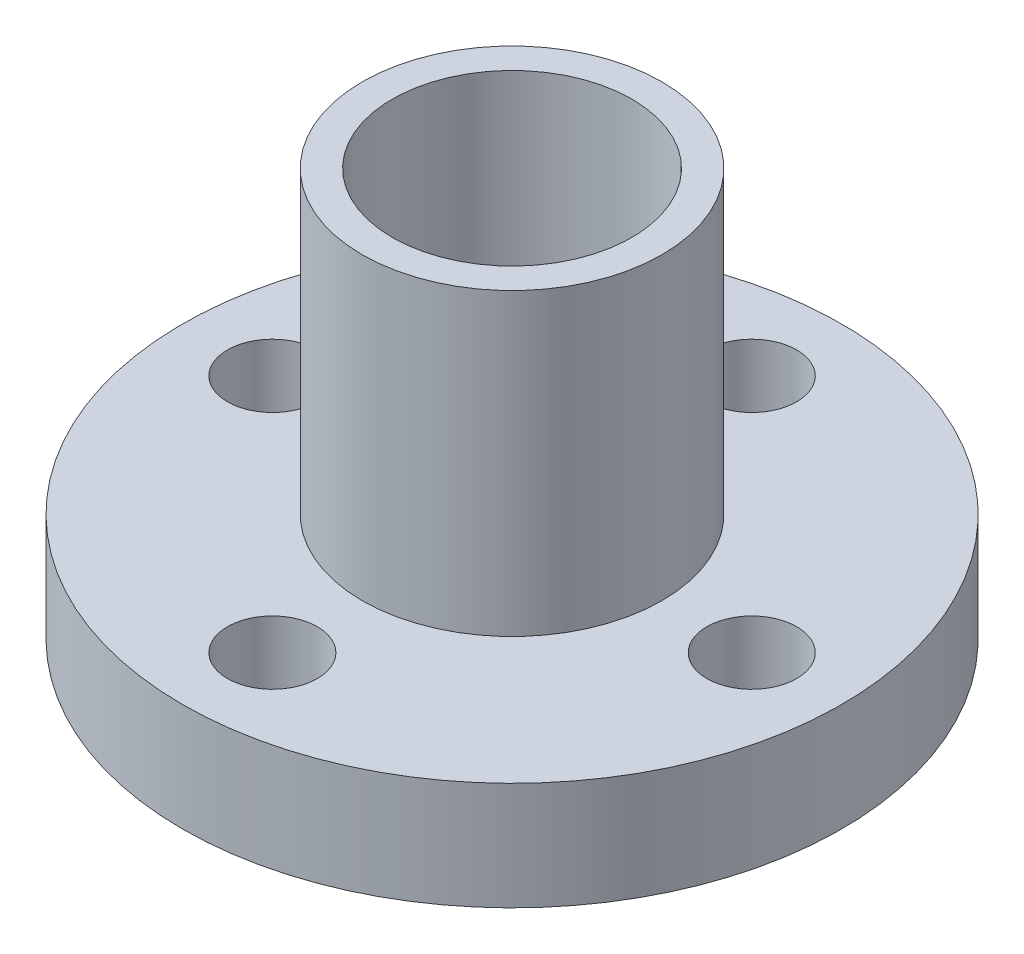
SolidWorks part; units mm, degrees
ref_plane "Front Plane" through (0, 0, 0) normal (0, 0, 1) x (1, 0, 0)
ref_plane "Top Plane" through (0, 0, 0) normal (0, 1, 0) x (1, 0, 0)
ref_plane "Right Plane" through (0, 0, 0) normal (1, 0, 0) x (0, 0, -1)
sketch "Sketch1" plane through (0, 0, 0) normal (0, 1, 0) x (1, 0, 0)
  circle A0 centre (0, 0) radius 11
  dimension "D1" = 22
extrude "Boss-Extrude1" add sketch "Sketch1" along normal blind 3.6
sketch "Sketch2" plane through (0, 3.6, 0) normal (0, 1, 0) x (1, 0, 0)
  circle A0 centre (0, 0) radius 5
  dimension "D1" = 10
extrude "Boss-Extrude2" add sketch "Sketch2" along normal blind 10 contours A0
sketch "Sketch3" plane through (0, 0, 0) normal (0, -1, 0) x (1, 0, 0)
  circle A0 centre (0, 0) radius 5
  dimension "D1" = 10
extrude "Boss-Extrude3" add sketch "Sketch3" along normal blind 1.5
sketch "Sketch4" plane through (0, 13.6, 0) normal (0, 1, 0) x (1, 0, 0)
  circle A0 centre (0, 0) radius 4
  dimension "D1" = 8
extrude "Cut-Extrude1" cut sketch "Sketch4" against normal through all contours A0
sketch "Sketch5" plane through (0, 3.6, 0) normal (0, 1, 0) x (1, 0, 0)
  line L0 (0, 5) -> (0, 11) construction
  circle A0 centre (0, 8) radius 1.5
  circle A1 centre (0, 0) radius 5 construction
  circle A2 centre (0, 0) radius 11 construction
  point P12 (0, 8)
  dimension "D1" = 3
extrude "Cut-Extrude2" cut sketch "Sketch5" against normal through all both and the other way through all contours A0
pattern_circular "CirPattern1" count 4 over 360 about axis through (0, 0, 0) along (0, 1, 0) of "Cut-Extrude2"
